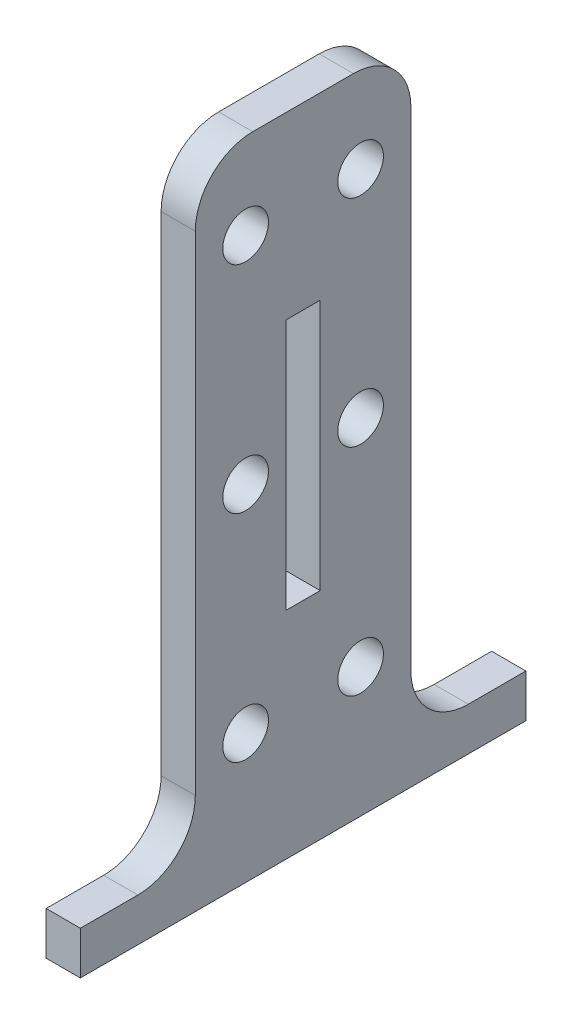
SolidWorks part; units mm, degrees
material "AISI 1020"
ref_plane "Plano frontal" through (0, 0, 0) normal (0, 0, 1) x (1, 0, 0)
ref_plane "Plano superior" through (0, 0, 0) normal (0, 1, 0) x (1, 0, 0)
ref_plane "Plano direito" through (0, 0, 0) normal (1, 0, 0) x (0, 0, -1)
sketch "Esboço1" plane through (0, 0, 0) normal (0, 0, 1) x (1, 0, 0)
  line L0 (0, 0) -> (0, 100)
  line L1 (0, 100) -> (60, 0)
  line L2 (60, 0) -> (0, 0)
  dimension "D1" = 100
  dimension "D2" = 60
extrude "Ressalto-extrusão1" add sketch "Esboço1" along normal blind 30
ref_plane "Plano1" through (6, 0, 0) normal (-1, 0, 0) x (0, 0, 1)
sketch "Esboço2" plane through (6, 0, 0) normal (-1, 0, 0) x (0, 0, 1)
  line L0 (30, 100) -> (0, 100) construction
  line L1 (18, 100) -> (30, 100)
  line L2 (18, 100) -> (18, 6)
  line L3 (18, 6) -> (30, 6)
  line L4 (30, 100) -> (30, 6)
  line L5 (0, 0) -> (0, 100) construction
  line L6 (12, 100) -> (0, 100)
  line L7 (12, 100) -> (12, 6)
  line L8 (12, 6) -> (0, 6)
  line L9 (0, 100) -> (0, 6)
  line L10 (30, 0) -> (0, 0) construction
  line L11 (30, 0) -> (30, 100) construction
  line L12 (18, 6) -> (12, 6) construction
  line L13 (15, 6) -> (15, 0) construction
  dimension "D1" = 6
  dimension "D2" = 6
extrude "Corte-extrusão1" cut sketch "Esboço2" against normal through all
sketch "Esboço3" plane through (6, 0, 0) normal (1, 0, 0) x (0, 0, -1)
  line L1 (-30, 90) -> (0, 90)
  line L2 (-30, 90) -> (-30, 100)
  line L3 (-30, 100) -> (0, 100)
  line L4 (0, 90) -> (0, 100)
extrude "Corte-extrusão2" cut sketch "Esboço3" against normal through all
sketch "Esboço4" plane through (0, 6, 0) normal (0, 1, 0) x (1, 0, 0)
  line L1 (56.4, 0) -> (60, 0)
  line L2 (56.4, 0) -> (56.4, -30)
  line L3 (56.4, -30) -> (60, -30)
  line L4 (60, 0) -> (60, -30)
extrude "Corte-extrusão3" cut sketch "Esboço4" against normal through all
sketch "Esboço5" plane through (0, 0, 30) normal (0, 0, 1) x (1, 0, 0)
  line L1 (56.4, 6) -> (0, 6)
  line L2 (56.4, 6) -> (56.4, 0)
  line L3 (56.4, 0) -> (0, 0)
  line L4 (0, 6) -> (0, 0)
extrude "Ressalto-extrusão2" add sketch "Esboço5" along normal blind 16
sketch "Esboço6" plane through (0, 0, 0) normal (0, 0, -1) x (-1, 0, 0)
  line L1 (-56.4, 6) -> (0, 6)
  line L2 (-56.4, 6) -> (-56.4, 0)
  line L3 (-56.4, 0) -> (0, 0)
  line L4 (0, 6) -> (0, 0)
extrude "Ressalto-extrusão3" add sketch "Esboço6" along normal blind 16
fillet "Filete1" radius 8 2 edges at (3, 6, 30) (3, 6, 0)
fillet "Filete2" radius 8 2 edges at (56.4, 3, -16) (56.4, 3, 46)
fillet "Filete3" radius 8 2 edges at (3, 90, 30) (3, 90, 0)
fillet "Filete4" radius 4 2 edges at (31.2, 6, 18) (31.2, 6, 12)
sketch "Esboço7" plane through (6, 0, 0) normal (1, 0, 0) x (0, 0, -1)
  line L0 (-15, 90) -> (-15, 0) construction
  line L1 (-18, 90) -> (-12, 90) construction
  line L2 (8, 0) -> (-38, 0) construction
  line L3 (-22, 90) -> (-18, 90) construction
  circle A0 centre (-23, 78) radius 3.175
  circle A1 centre (-23, 48) radius 3.175
  circle A2 centre (-23, 18) radius 3.175
  circle A3 centre (-7, 18) radius 3.175
  circle A4 centre (-7, 48) radius 3.175
  circle A5 centre (-7, 78) radius 3.175
  dimension "D1" = 30
  dimension "D2" = 30
  dimension "D4" = 6.35
  dimension "D5" = 12
  dimension "D3" = 8
extrude "Corte-extrusão4" cut sketch "Esboço7" against normal through all
sketch "Esboço8" plane through (0, 6, 0) normal (0, 1, 0) x (1, 0, 0)
  line L0 (48.4, -15) -> (56.4, -15) construction
  line L1 (16.4, 8) -> (48.4, 8) construction
  line L2 (16.4, 8) -> (16.4, -38) construction
  line L3 (16.4, -38) -> (48.4, -38) construction
  line L4 (48.4, 8) -> (48.4, -38) construction
  line L5 (56.4, -8) -> (56.4, -22) construction
  circle A0 centre (48.4, 8) radius 3.25
  circle A1 centre (48.4, -38) radius 3.25
  circle A2 centre (16.4, -38) radius 3.25
  circle A3 centre (16.4, 8) radius 3.25
  dimension "D4" = 6.5
  dimension "D1" = 8
  dimension "D2" = 32
  dimension "D3" = 46
extrude "Corte-extrusão5" cut sketch "Esboço8" against normal through all
sketch "Esboço9" plane through (6, 0, 0) normal (1, 0, 0) x (0, 0, -1)
  line L0 (-18, 90) -> (-12, 90) construction
  line L1 (16, 0) -> (-46, 0)
  line L2 (16, 0) -> (16, 90)
  line L3 (16, 90) -> (-46, 90)
  line L4 (-46, 0) -> (-46, 90)
  point P5 (-46, 0)
extrude "Corte-extrusão6" cut sketch "Esboço9" against normal blind 1.24 and the other way through all
sketch "Esboço10" plane through (0, 0, 0) normal (-1, 0, 0) x (0, 0, 1)
  line L0 (46, 0) -> (-16, 0) construction
  line L1 (17.38, -65) -> (12.62, -65)
  line L2 (17.38, -65) -> (17.38, 65)
  line L3 (17.38, 65) -> (12.62, 65)
  line L4 (12.62, -65) -> (12.62, 65)
  line L5 (17.38, -65) -> (12.62, 65) construction
  line L6 (17.38, 65) -> (12.62, -65) construction
  line L7 (22, 90) -> (8, 90) construction
  point P0 (15, 0)
  dimension "D1" = 4.76
  dimension "D2" = 25
extrude "Corte-extrusão7" cut sketch "Esboço10" against normal through all
sketch "Esboço11" plane through (0, 0, 0) normal (-1, 0, 0) x (0, 0, 1)
  line L0 (17.38, 0) -> (17.38, 65) construction
  line L1 (12.62, 0) -> (17.38, 0)
  line L2 (12.62, 0) -> (12.62, 30)
  line L3 (12.62, 30) -> (17.38, 30)
  line L4 (17.38, 0) -> (17.38, 30)
  dimension "D1" = 30
extrude "Ressalto-extrusão4" add sketch "Esboço11" against normal through all contours L3 L4 L1 L2
